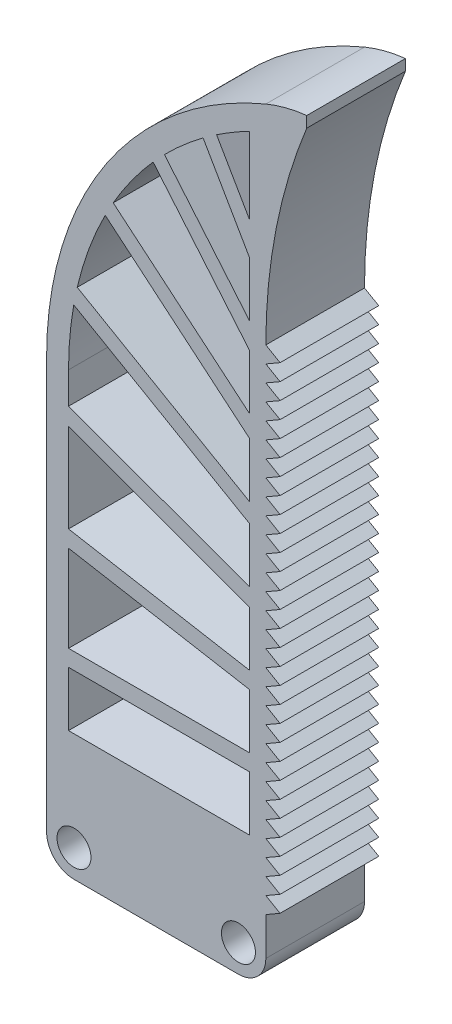
SolidWorks part; units mm, degrees
ref_plane "Front Plane" through (0, 0, 0) normal (0, 0, 1) x (1, 0, 0)
ref_plane "Top Plane" through (0, 0, 0) normal (0, 1, 0) x (1, 0, 0)
ref_plane "Right Plane" through (0, 0, 0) normal (1, 0, 0) x (0, 0, -1)
sketch "Sketch2" plane through (0, 0, 0) normal (0, 0, 1) x (1, 0, 0)
  line L0 (-20, 0) -> (20, 0)
  line L5 (20, 0) -> (20, 140)
  line L10 (-20, 0) -> (-20, 80)
  arc A0 (20, 140) -> (-20, 80) centre (45, 80) ccw
  dimension "D4" = 40
  dimension "D5" = 140
  dimension "D6" = 80
extrude "Boss-Extrude1" add sketch "Sketch2" along normal blind 18
sketch "Sketch3" plane through (0, 0, 18) normal (0, 0, 1) x (1, 0, 0)
  line L0 (-16, 23) -> (17, 23)
  line L1 (17, 23) -> (17, 33)
  line L2 (17, 33) -> (-16, 33)
  line L3 (-16, 33) -> (-16, 23)
  line L4 (-20, 80) -> (-20, 0) construction
  line L5 (20, 0) -> (20, 140) construction
  line L7 (-20, 0) -> (20, 0) construction
  dimension "D1" = 4
  dimension "D2" = 3
  dimension "D3" = 23
  dimension "D4" = 10
sketch "Sketch4" plane through (0, 0, 18) normal (0, 0, 1) x (1, 0, 0)
  line L0 (-16, 36) -> (17, 36)
  line L1 (17, 36) -> (17, 46)
  line L2 (17, 46) -> (-16, 51.8188)
  line L3 (-16, 51.8188) -> (-16, 36)
  line L4 (-20, 80) -> (-20, 0) construction
  line L5 (17, 33) -> (-16, 33) construction
  line L6 (20, 0) -> (20, 140) construction
  dimension "D1" = 4
  dimension "D2" = 3
  dimension "D3" = 3
  dimension "D4" = 10
  dimension "D5" = 10
sketch "Sketch5" plane through (0, 0, 18) normal (0, 0, 1) x (1, 0, 0)
  line L0 (-16, 54.8651) -> (17, 49.0463)
  line L1 (17, 49.0463) -> (17, 59.0463)
  line L2 (17, 59.0463) -> (-16, 71.0573)
  line L3 (-16, 71.0573) -> (-16, 54.8651)
  line L4 (-20, 80) -> (-20, 0) construction
  line L5 (20, 0) -> (20, 140) construction
  line L7 (17, 46) -> (-16, 51.8188) construction
  line L8 (-16, 36) -> (17, 36) construction
  dimension "D1" = 4
  dimension "D2" = 3
  dimension "D3" = 3
  dimension "D4" = 20
  dimension "D5" = 10
sketch "Sketch6" plane through (0, 0, 18) normal (0, 0, 1) x (1, 0, 0)
  line L0 (-16, 74.2498) -> (17, 62.2388)
  line L1 (17, 62.2388) -> (17, 72.2388)
  line L2 (17, 72.2388) -> (-15.0469, 90.7411)
  line L3 (-16, 74.2498) -> (-16, 80)
  line L5 (17, 59.0463) -> (-16, 71.0573) construction
  line L6 (-20, 80) -> (-20, 0) construction
  line L7 (20, 0) -> (20, 140) construction
  line L8 (-16, 36) -> (17, 36) construction
  arc A0 (-15.0469, 90.7411) -> (-16, 80) centre (45, 80) ccw
  arc A2 (20, 140) -> (-20, 80) centre (45, 80) ccw construction
  dimension "D1" = 3
  dimension "D2" = 4
  dimension "D3" = 3
  dimension "D4" = 30
  dimension "D5" = 10
extrude "Cut-Extrude1" cut sketch "Sketch3" against normal through all contours L0 L1 L2 L3
extrude "Cut-Extrude2" cut sketch "Sketch4" against normal through all contours L0 L1 L2 L3
extrude "Cut-Extrude3" cut sketch "Sketch5" against normal through all contours L0 L1 L2 L3
extrude "Cut-Extrude4" cut sketch "Sketch6" against normal through all contours L0 L1 L2 A0 L3
sketch "Sketch13" plane through (0, 0, 18) normal (0, 0, 1) x (1, 0, 0)
  line L0 (20, 0) -> (20, 140) construction
  line L1 (27.4639, 141.9193) -> (27.4639, 139.9193)
  line L2 (20, 140) -> (20, 101.9347)
  arc A0 (20, 140) -> (27.4639, 141.9193) centre (30.3921, 115.059) cw
  arc A1 (20, 101.9347) -> (27.4639, 139.9193) centre (120.3863, 101.9347) cw
  arc A2 (20, 140) -> (-20, 80) centre (45, 80) ccw construction
  dimension "D1" = 2
extrude "Boss-Extrude2" add sketch "Sketch13" against normal up to surface (18 mm away) up to face at (-2.2708, 56.5139, 0)
sketch "Sketch15" plane through (0, 0, 18) normal (0, 0, 1) x (1, 0, 0)
  line L0 (20, 101.9347) -> (22.5981, 100.4347)
  line L1 (22.5981, 100.4347) -> (20, 98.9347)
  line L2 (20, 0) -> (20, 101.9347) construction
  line L3 (20, 101.9347) -> (20, 98.9347)
  dimension "D1" = 3
  dimension "D2" = 3
  dimension "D3" = 3
extrude "Boss-Extrude3" add sketch "Sketch15" against normal up to surface (18 mm away) up to face at (9.1325, 87.2085, 0)
pattern_linear "LPattern1" count 30 spacing 3 along (0, -1, 0) of "Boss-Extrude3"
sketch "Sketch17" plane through (0, 0, 18) normal (0, 0, 1) x (1, 0, 0)
  line L0 (-14.4098, 93.8374) -> (17, 75.7029)
  line L1 (17, 75.7029) -> (17, 85.7029)
  line L2 (17, 85.7029) -> (-9.3082, 107.7781)
  line L3 (17, 72.2388) -> (-15.0469, 90.7411) construction
  line L4 (17, 62.2388) -> (17, 72.2388) construction
  arc A0 (-9.3082, 107.7781) -> (-14.4098, 93.8374) centre (45, 80) ccw
  arc A1 (-15.0469, 90.7411) -> (-16, 80) centre (45, 80) ccw construction
  dimension "D1" = 10
  dimension "D2" = 3
  dimension "D3" = 10
extrude "Cut-Extrude5" cut sketch "Sketch17" against normal through all contours L2 A0 L0 L1
sketch "Sketch18" plane through (0, 0, 18) normal (0, 0, 1) x (1, 0, 0)
  line L0 (-7.8462, 110.4676) -> (17, 89.6191)
  line L1 (17, 89.6191) -> (17, 99.6191)
  line L2 (17, 99.6191) -> (-0.5668, 120.5545)
  line L3 (17, 85.7029) -> (-9.3082, 107.7781) construction
  line L4 (17, 75.7029) -> (17, 85.7029) construction
  arc A0 (-0.5668, 120.5545) -> (-7.8462, 110.4676) centre (45, 80) ccw
  arc A1 (-9.3082, 107.7781) -> (-14.4098, 93.8374) centre (45, 80) ccw construction
  dimension "D1" = 3
  dimension "D2" = 10
  dimension "D3" = 10
extrude "Cut-Extrude6" cut sketch "Sketch18" against normal through all
sketch "Sketch19" plane through (0, 0, 18) normal (0, 0, 1) x (1, 0, 0)
  line L0 (1.4976, 122.7614) -> (17, 104.2863)
  line L1 (17, 104.2863) -> (17, 114.2863)
  line L2 (17, 114.2863) -> (8.554, 128.9151)
  line L3 (17, 89.6191) -> (17, 99.6191) construction
  line L5 (17, 99.6191) -> (-0.5668, 120.5545) construction
  arc A0 (8.554, 128.9151) -> (1.4976, 122.7614) centre (45, 80) ccw
  arc A1 (-0.5668, 120.5545) -> (-7.8462, 110.4676) centre (45, 80) ccw construction
  dimension "D1" = 10
  dimension "D2" = 3
  dimension "D3" = 10
extrude "Cut-Extrude7" cut sketch "Sketch19" against normal through all contours L2 A0 L0 L1
sketch "Sketch21" plane through (0, 0, 18) normal (0, 0, 1) x (1, 0, 0)
  line L0 (11.0136, 130.655) -> (17, 120.2863)
  line L1 (17, 120.2863) -> (17, 134.1941)
  line L3 (17, 114.2863) -> (8.554, 128.9151) construction
  line L4 (17, 104.2863) -> (17, 114.2863) construction
  arc A0 (17, 134.1941) -> (11.0136, 130.655) centre (45, 80) ccw
  arc A1 (8.554, 128.9151) -> (1.4976, 122.7614) centre (45, 80) ccw construction
  dimension "D2" = 3
extrude "Cut-Extrude8" cut sketch "Sketch21" against normal through all
fillet "Fillet1" radius 5 2 edges at (20, 0, 9) (-20, 0, 9)
hole_wizard "Ø6.0 mm Dowel Holes1" positions "Sketch22" profile "Sketch23" hole size "Ø6.0" standard "ISO" end condition through all
sketch "Sketch22" plane through (0, 0, 18) normal (0, 0, 1) x (1, 0, 0)
  point P0 (-15, 5)
sketch "Sketch23" plane through (-15, 5, 18) normal (1, 0, 0) x (0, -1, 0)
  line L0 (0, 0) -> (0, 18)
  line L1 (0, 18) -> (3.1, 18)
  line L2 (3.1, 18) -> (3.1, 0)
  line L5 (3.1, 0) -> (0, 0)
  line L11 (0, -6.35) -> (0, 107.95) construction
  dimension "Thru Hole Dia." = 6.2
  dimension "Thru Hole Depth" = 18
mirror "Mirror1" about plane through (0, 0, 0) normal (1, 0, 0) of "Ø6.0 mm Dowel Holes1"
